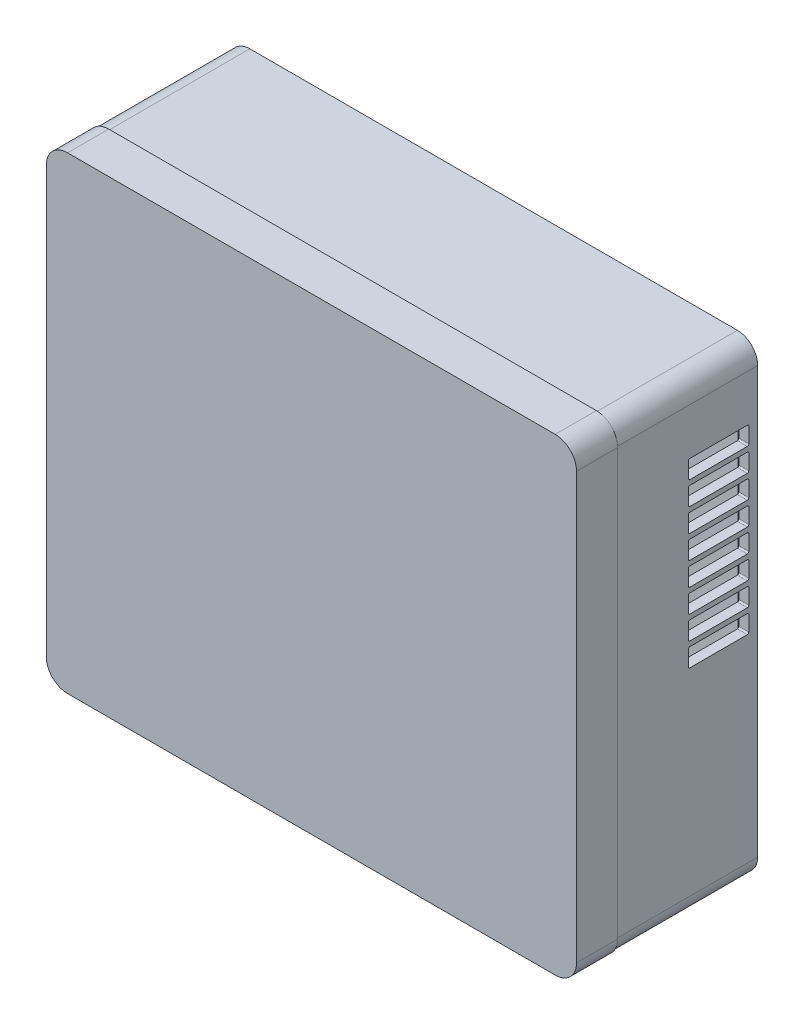
SolidWorks part; units mm, degrees
ref_plane "Front Plane" through (0, 0, 0) normal (0, 0, 1) x (1, 0, 0)
ref_plane "Top Plane" through (0, 0, 0) normal (0, 1, 0) x (1, 0, 0)
ref_plane "Right Plane" through (0, 0, 0) normal (1, 0, 0) x (0, 0, -1)
sketch "Sketch1" plane through (0, 0, 0) normal (0, 0, 1) x (1, 0, 0)
  line L4 (-86.3, 47.45) -> (-86.3, -38.45)
  line L5 (-84, -40.75) -> (14.4, -40.75)
  line L6 (16.7, -38.45) -> (16.7, 47.45)
  line L7 (14.4, 49.75) -> (-84, 49.75)
  line L8 (-86.3, 47.45) -> (-86.3, -38.45)
  line L9 (-84, -40.75) -> (14.4, -40.75)
  line L10 (16.7, -38.45) -> (16.7, 47.45)
  line L11 (14.4, 49.75) -> (-84, 49.75)
  arc A4 (-86.3, -38.45) -> (-84, -40.75) centre (-84, -38.45) ccw
  arc A5 (14.4, -40.75) -> (16.7, -38.45) centre (14.4, -38.45) ccw
  arc A6 (16.7, 47.45) -> (14.4, 49.75) centre (14.4, 47.45) ccw
  arc A7 (-84, 49.75) -> (-86.3, 47.45) centre (-84, 47.45) ccw
  arc A8 (-86.3, -38.45) -> (-84, -40.75) centre (-84, -38.45) ccw
  arc A9 (14.4, -40.75) -> (16.7, -38.45) centre (14.4, -38.45) ccw
  arc A10 (16.7, 47.45) -> (14.4, 49.75) centre (14.4, 47.45) ccw
  arc A11 (-84, 49.75) -> (-86.3, 47.45) centre (-84, 47.45) ccw
  dimension "D1" = 0
extrude "Boss-Extrude1" add sketch "Sketch1" along normal blind 2
sketch "Sketch2" plane through (0, 0, 2) normal (0, 0, 1) x (1, 0, 0)
  line L8 (-88.3, 47.45) -> (-88.3, -38.45)
  line L9 (-84, -42.75) -> (14.4, -42.75)
  line L10 (18.7, -38.45) -> (18.7, 47.45)
  line L11 (14.4, 51.75) -> (-84, 51.75)
  line L12 (-88.3, 47.45) -> (-88.3, -38.45)
  line L13 (-84, -42.75) -> (14.4, -42.75)
  line L14 (18.7, -38.45) -> (18.7, 47.45)
  line L15 (14.4, 51.75) -> (-84, 51.75)
  arc A8 (-84, 51.75) -> (-88.3, 47.45) centre (-84, 47.45) ccw
  arc A9 (-88.3, -38.45) -> (-84, -42.75) centre (-84, -38.45) ccw
  arc A10 (14.4, -42.75) -> (18.7, -38.45) centre (14.4, -38.45) ccw
  arc A11 (18.7, 47.45) -> (14.4, 51.75) centre (14.4, 47.45) ccw
  arc A12 (-84, 51.75) -> (-88.3, 47.45) centre (-84, 47.45) ccw
  arc A13 (-88.3, -38.45) -> (-84, -42.75) centre (-84, -38.45) ccw
  arc A14 (14.4, -42.75) -> (18.7, -38.45) centre (14.4, -38.45) ccw
  arc A15 (18.7, 47.45) -> (14.4, 51.75) centre (14.4, 47.45) ccw
  dimension "D1" = 2
extrude "Boss-Extrude2" add sketch "Sketch2" against normal blind 8.3
sketch "Sketch3" plane through (0, 0, -34.766) normal (0, 0, -1) x (-1, 0, 0)
  line L4 (-14.4, -40.55) -> (84, -40.55)
  line L5 (86.1, -38.45) -> (86.1, 47.45)
  line L6 (84, 49.55) -> (-14.4, 49.55)
  line L7 (-16.5, 47.45) -> (-16.5, -38.45)
  line L8 (-14.4, -40.55) -> (84, -40.55)
  line L9 (86.1, -38.45) -> (86.1, 47.45)
  line L10 (84, 49.55) -> (-14.4, 49.55)
  line L11 (-16.5, 47.45) -> (-16.5, -38.45)
  line L12 (61.7, 0.56) -> (61.7, 38.96)
  line L13 (61.7, 38.96) -> (3.9, 38.96)
  line L14 (3.9, 38.96) -> (3.9, 0.56)
  line L15 (3.9, 0.56) -> (61.7, 0.56)
  line L16 (61.7, 0.56) -> (61.7, 38.96)
  line L17 (61.7, 38.96) -> (3.9, 38.96)
  line L18 (3.9, 38.96) -> (3.9, 0.56)
  line L19 (3.9, 0.56) -> (61.7, 0.56)
  arc A4 (84, -40.55) -> (86.1, -38.45) centre (84, -38.45) ccw
  arc A5 (86.1, 47.45) -> (84, 49.55) centre (84, 47.45) ccw
  arc A6 (-14.4, 49.55) -> (-16.5, 47.45) centre (-14.4, 47.45) ccw
  arc A7 (-16.5, -38.45) -> (-14.4, -40.55) centre (-14.4, -38.45) ccw
  arc A8 (84, -40.55) -> (86.1, -38.45) centre (84, -38.45) ccw
  arc A9 (86.1, 47.45) -> (84, 49.55) centre (84, 47.45) ccw
  arc A10 (-14.4, 49.55) -> (-16.5, 47.45) centre (-14.4, 47.45) ccw
  arc A11 (-16.5, -38.45) -> (-14.4, -40.55) centre (-14.4, -38.45) ccw
  dimension "D1" = 0
  dimension "D2" = 0
extrude "Boss-Extrude3" add sketch "Sketch3" against normal blind 2 separate body
sketch "Sketch4" plane through (0, 0, -34.766) normal (0, 0, -1) x (-1, 0, 0)
  line L8 (-14.4, -42.55) -> (84, -42.55)
  line L9 (88.1, -38.45) -> (88.1, 47.45)
  line L10 (84, 51.55) -> (-14.4, 51.55)
  line L11 (-18.5, 47.45) -> (-18.5, -38.45)
  line L12 (-14.4, -42.55) -> (84, -42.55)
  line L13 (88.1, -38.45) -> (88.1, 47.45)
  line L14 (84, 51.55) -> (-14.4, 51.55)
  line L15 (-18.5, 47.45) -> (-18.5, -38.45)
  line L16 (61.7, 0.56) -> (61.7, 38.96)
  line L17 (61.7, 38.96) -> (3.9, 38.96)
  line L18 (3.9, 38.96) -> (3.9, 0.56)
  line L19 (3.9, 0.56) -> (61.7, 0.56)
  line L20 (61.7, 0.56) -> (61.7, 38.96)
  line L21 (61.7, 38.96) -> (3.9, 38.96)
  line L22 (3.9, 38.96) -> (3.9, 0.56)
  line L23 (3.9, 0.56) -> (61.7, 0.56)
  line L24 (-14.4, -40.55) -> (84, -40.55)
  line L25 (86.1, -38.45) -> (86.1, 47.45)
  line L26 (84, 49.55) -> (-14.4, 49.55)
  line L27 (-16.5, 47.45) -> (-16.5, -38.45)
  line L28 (-14.4, -40.55) -> (84, -40.55)
  line L29 (86.1, -38.45) -> (86.1, 47.45)
  line L30 (84, 49.55) -> (-14.4, 49.55)
  line L31 (-16.5, 47.45) -> (-16.5, -38.45)
  arc A8 (-18.5, -38.45) -> (-14.4, -42.55) centre (-14.4, -38.45) ccw
  arc A9 (84, -42.55) -> (88.1, -38.45) centre (84, -38.45) ccw
  arc A10 (88.1, 47.45) -> (84, 51.55) centre (84, 47.45) ccw
  arc A11 (-14.4, 51.55) -> (-18.5, 47.45) centre (-14.4, 47.45) ccw
  arc A12 (-18.5, -38.45) -> (-14.4, -42.55) centre (-14.4, -38.45) ccw
  arc A13 (84, -42.55) -> (88.1, -38.45) centre (84, -38.45) ccw
  arc A14 (88.1, 47.45) -> (84, 51.55) centre (84, 47.45) ccw
  arc A15 (-14.4, 51.55) -> (-18.5, 47.45) centre (-14.4, 47.45) ccw
  arc A16 (-16.5, -38.45) -> (-14.4, -40.55) centre (-14.4, -38.45) ccw
  arc A17 (84, -40.55) -> (86.1, -38.45) centre (84, -38.45) ccw
  arc A18 (86.1, 47.45) -> (84, 49.55) centre (84, 47.45) ccw
  arc A19 (-14.4, 49.55) -> (-16.5, 47.45) centre (-14.4, 47.45) ccw
  arc A20 (-16.5, -38.45) -> (-14.4, -40.55) centre (-14.4, -38.45) ccw
  arc A21 (84, -40.55) -> (86.1, -38.45) centre (84, -38.45) ccw
  arc A22 (86.1, 47.45) -> (84, 49.55) centre (84, 47.45) ccw
  arc A23 (-14.4, 49.55) -> (-16.5, 47.45) centre (-14.4, 47.45) ccw
  arc M13 (-16.5, -38.45) -> (-14.4, -40.55) centre (-14.4, -38.45) ccw
  line M14 (-14.4, -40.55) -> (84, -40.55)
  arc M15 (84, -40.55) -> (86.1, -38.45) centre (84, -38.45) ccw
  line M16 (86.1, -38.45) -> (86.1, 47.45)
  arc M17 (86.1, 47.45) -> (84, 49.55) centre (84, 47.45) ccw
  line M18 (84, 49.55) -> (-14.4, 49.55)
  arc M19 (-14.4, 49.55) -> (-16.5, 47.45) centre (-14.4, 47.45) ccw
  line M20 (-16.5, 47.45) -> (-16.5, -38.45)
  dimension "D1" = 2
  dimension "D2" = 0
  dimension "D3" = 0
extrude "Boss-Extrude6" add sketch "Sketch4" along direction (0, 0, 1) on the side against the normal blind 30 contours L14 A15 L15 A12 L12 A13 L13 A14 M13 M20 M19 M18 M17 M16 M15 M14
sketch "Sketch5" plane through (0, -42.55, 0) normal (0, -1, 0) x (1, 0, 0)
  line L4 (13.85, -17.47) -> (13.85, -6.47)
  line L5 (13.85, -6.47) -> (4.55, -6.47)
  line L6 (4.55, -6.47) -> (4.55, -17.47)
  line L7 (4.55, -17.47) -> (13.85, -17.47)
  line L8 (13.85, -17.47) -> (13.85, -6.47)
  line L9 (13.85, -6.47) -> (4.55, -6.47)
  line L10 (4.55, -6.47) -> (4.55, -17.47)
  line L11 (4.55, -17.47) -> (13.85, -17.47)
  line L12 (1.288, -13.3562) -> (1.288, -6.5462)
  line L13 (1.288, -6.5462) -> (-16.408, -6.5462)
  line L14 (-16.408, -6.5462) -> (-16.408, -13.3562)
  line L15 (-16.408, -13.3562) -> (1.288, -13.3562)
  line L16 (1.288, -13.3562) -> (1.288, -6.5462)
  line L17 (1.288, -6.5462) -> (-16.408, -6.5462)
  line L18 (-16.408, -6.5462) -> (-16.408, -13.3562)
  line L19 (-16.408, -13.3562) -> (1.288, -13.3562)
  line L20 (-20.375, -23.3862) -> (-20.375, -6.5462)
  line L21 (-20.375, -6.5462) -> (-34.425, -6.5462)
  line L22 (-34.425, -6.5462) -> (-34.425, -23.3862)
  line L23 (-34.425, -23.3862) -> (-20.375, -23.3862)
  line L24 (-20.375, -23.3862) -> (-20.375, -6.5462)
  line L25 (-20.375, -6.5462) -> (-34.425, -6.5462)
  line L26 (-34.425, -6.5462) -> (-34.425, -23.3862)
  line L27 (-34.425, -23.3862) -> (-20.375, -23.3862)
  line L28 (-37.375, -23.3862) -> (-37.375, -6.5462)
  line L29 (-37.375, -6.5462) -> (-51.425, -6.5462)
  line L30 (-51.425, -6.5462) -> (-51.425, -23.3862)
  line L31 (-51.425, -23.3862) -> (-37.375, -23.3862)
  line L32 (-37.375, -23.3862) -> (-37.375, -6.5462)
  line L33 (-37.375, -6.5462) -> (-51.425, -6.5462)
  line L34 (-51.425, -6.5462) -> (-51.425, -23.3862)
  line L35 (-51.425, -23.3862) -> (-37.375, -23.3862)
  line L36 (-72.33, -9.9762) -> (-72.33, -6.5462)
  line L37 (-72.33, -6.5462) -> (-81.22, -6.5462)
  line L38 (-81.22, -6.5462) -> (-81.22, -9.9762)
  line L39 (-81.22, -9.9762) -> (-72.33, -9.9762)
  line L40 (-72.33, -9.9762) -> (-72.33, -6.5462)
  line L41 (-72.33, -6.5462) -> (-81.22, -6.5462)
  line L42 (-81.22, -6.5462) -> (-81.22, -9.9762)
  line L43 (-81.22, -9.9762) -> (-72.33, -9.9762)
  line L44 (-57.38, -20.12) -> (-57.38, -6.47)
  line L45 (-57.38, -6.47) -> (-66.12, -6.47)
  line L46 (-66.12, -6.47) -> (-66.12, -20.12)
  line L47 (-66.12, -20.12) -> (-57.38, -20.12)
  line L48 (-57.38, -20.12) -> (-57.38, -6.47)
  line L49 (-57.38, -6.47) -> (-66.12, -6.47)
  line L50 (-66.12, -6.47) -> (-66.12, -20.12)
  line L51 (-66.12, -20.12) -> (-57.38, -20.12)
  line L52 (-55.38, -20.12) -> (-55.38, -6.47)
  line L53 (-55.38, -6.47) -> (-57.38, -6.47)
  line L54 (-57.38, -6.47) -> (-57.38, -20.12)
  line L55 (-57.38, -20.12) -> (-55.38, -20.12)
  line L56 (-55.38, -20.12) -> (-55.38, -6.47)
  line L57 (-55.38, -6.47) -> (-57.38, -6.47)
  line L58 (-57.38, -6.47) -> (-57.38, -20.12)
  line L59 (-57.38, -20.12) -> (-55.38, -20.12)
  line L60 (-53.673, -20.12) -> (-53.673, -6.47)
  line L61 (-53.673, -6.47) -> (-55.38, -6.47)
  line L62 (-55.38, -6.47) -> (-55.38, -20.12)
  line L63 (-55.38, -20.12) -> (-53.673, -20.12)
  line L64 (-53.673, -20.12) -> (-53.673, -6.47)
  line L65 (-53.673, -6.47) -> (-55.38, -6.47)
  line L66 (-55.38, -6.47) -> (-55.38, -20.12)
  line L67 (-55.38, -20.12) -> (-53.673, -20.12)
  line L68 (-66.12, -20.12) -> (-66.12, -6.47)
  line L69 (-66.12, -6.47) -> (-68.12, -6.47)
  line L70 (-68.12, -6.47) -> (-68.12, -20.12)
  line L71 (-68.12, -20.12) -> (-66.12, -20.12)
  line L72 (-66.12, -20.12) -> (-66.12, -6.47)
  line L73 (-66.12, -6.47) -> (-68.12, -6.47)
  line L74 (-68.12, -6.47) -> (-68.12, -20.12)
  line L75 (-68.12, -20.12) -> (-66.12, -20.12)
  line L76 (-68.12, -20.12) -> (-68.12, -6.47)
  line L77 (-68.12, -6.47) -> (-69.827, -6.47)
  line L78 (-69.827, -6.47) -> (-69.827, -20.12)
  line L79 (-69.827, -20.12) -> (-68.12, -20.12)
  line L80 (-68.12, -20.12) -> (-68.12, -6.47)
  line L81 (-68.12, -6.47) -> (-69.827, -6.47)
  line L82 (-69.827, -6.47) -> (-69.827, -20.12)
  line L83 (-69.827, -20.12) -> (-68.12, -20.12)
  dimension "D1" = 0
  dimension "D2" = 0
  dimension "D3" = 0
  dimension "D4" = 0
  dimension "D5" = 0
  dimension "D6" = 0
  dimension "D7" = 0
  dimension "D8" = 0
  dimension "D9" = 0
  dimension "D10" = 0
extrude "Cut-Extrude1" cut sketch "Sketch5" against normal blind 2 contours L26 L27 L24 L25 | L18 L19 L16 L17 | L10 L11 L8 L9 | L34 L35 L32 L33 | L50 L51 L48 L49 | L42 L43 L40 L41 | L82 L83 L74 L81 | L74 L75 L50 L73 | L56 L67 L64 L65
sketch "Sketch6" plane through (18.5, 0, 0) normal (1, 0, 0) x (0, 0, -1)
  line L0 (32.966, 1.76) -> (32.966, 4.86) construction
  line L1 (32.666, 1.46) -> (21.066, 1.46) construction
  line L2 (32.666, 5.16) -> (21.066, 5.16) construction
  line L3 (20.766, 4.86) -> (20.766, 1.76) construction
  line L4 (32.966, 1.76) -> (32.966, 4.86)
  line L5 (32.666, 1.46) -> (21.066, 1.46)
  line L6 (32.666, 5.16) -> (21.066, 5.16)
  line L7 (20.766, 4.86) -> (20.766, 1.76)
  arc A0 (32.966, 4.86) -> (32.666, 5.16) centre (32.666, 4.86) ccw construction
  arc A1 (32.666, 1.46) -> (32.966, 1.76) centre (32.666, 1.76) ccw construction
  arc A2 (20.766, 1.76) -> (21.066, 1.46) centre (21.066, 1.76) ccw construction
  arc A3 (21.066, 5.16) -> (20.766, 4.86) centre (21.066, 4.86) ccw construction
  arc A4 (32.966, 4.86) -> (32.666, 5.16) centre (32.666, 4.86) ccw
  arc A5 (32.666, 1.46) -> (32.966, 1.76) centre (32.666, 1.76) ccw
  arc A6 (20.766, 1.76) -> (21.066, 1.46) centre (21.066, 1.76) ccw
  arc A7 (21.066, 5.16) -> (20.766, 4.86) centre (21.066, 4.86) ccw
extrude "Cut-Extrude2" cut sketch "Sketch6" against normal blind 2
sketch "Sketch7" plane through (18.5, 0, 0) normal (1, 0, 0) x (0, 0, -1)
  line L1 (32.666, 28.66) -> (21.066, 28.66) construction
  line L2 (32.966, 25.26) -> (32.966, 28.36) construction
  line L3 (32.666, 24.96) -> (21.066, 24.96) construction
  line L4 (32.966, 20.56) -> (32.966, 23.66) construction
  line L5 (32.666, 23.96) -> (21.066, 23.96) construction
  line L6 (32.666, 20.26) -> (21.066, 20.26) construction
  line L7 (32.966, 15.86) -> (32.966, 18.96) construction
  line L8 (32.666, 15.56) -> (21.066, 15.56) construction
  line L9 (20.766, 18.96) -> (20.766, 15.86) construction
  line L10 (32.666, 19.26) -> (21.066, 19.26) construction
  line L11 (32.966, 11.16) -> (32.966, 14.26) construction
  line L12 (20.766, 14.26) -> (20.766, 11.16) construction
  line L13 (20.766, 12.3089) -> (20.766, 14.6156) construction
  line L14 (32.666, 14.56) -> (21.066, 14.56) construction
  line L15 (32.666, 10.86) -> (21.066, 10.86) construction
  line L16 (32.966, 6.46) -> (32.966, 9.56) construction
  line L17 (32.666, 9.86) -> (21.066, 9.86) construction
  line L18 (20.766, 9.56) -> (20.766, 6.46) construction
  line L19 (32.666, 6.16) -> (21.066, 6.16) construction
  line L20 (20.766, 28.36) -> (20.766, 25.26)
  line L21 (32.666, 28.66) -> (21.066, 28.66)
  line L22 (32.966, 25.26) -> (32.966, 28.36)
  line L23 (32.666, 24.96) -> (21.066, 24.96)
  line L24 (32.966, 20.56) -> (32.966, 23.66)
  line L25 (32.666, 23.96) -> (21.066, 23.96)
  line L26 (32.666, 20.26) -> (21.066, 20.26)
  line L27 (32.966, 15.86) -> (32.966, 18.96)
  line L28 (32.666, 15.56) -> (21.066, 15.56)
  line L29 (20.766, 18.96) -> (20.766, 15.86)
  line L30 (32.666, 19.26) -> (21.066, 19.26)
  line L31 (32.966, 11.16) -> (32.966, 14.26)
  line L32 (20.766, 14.26) -> (20.766, 11.16)
  line L33 (20.766, 12.3089) -> (20.766, 14.6156)
  line L34 (32.666, 14.56) -> (21.066, 14.56)
  line L35 (32.666, 10.86) -> (21.066, 10.86)
  line L36 (32.966, 6.46) -> (32.966, 9.56)
  line L37 (32.666, 9.86) -> (21.066, 9.86)
  line L38 (20.766, 9.56) -> (20.766, 6.46)
  line L39 (32.666, 6.16) -> (21.066, 6.16)
  line L40 (20.766, 23.66) -> (20.766, 20.56)
  arc A0 (21.066, 28.66) -> (20.766, 28.36) centre (21.066, 28.36) ccw construction
  arc A1 (32.966, 28.36) -> (32.666, 28.66) centre (32.666, 28.36) ccw construction
  arc A2 (32.666, 24.96) -> (32.966, 25.26) centre (32.666, 25.26) ccw construction
  arc A3 (32.966, 23.66) -> (32.666, 23.96) centre (32.666, 23.66) ccw construction
  arc A4 (32.666, 20.26) -> (32.966, 20.56) centre (32.666, 20.56) ccw construction
  arc A5 (20.766, 25.26) -> (21.066, 24.96) centre (21.066, 25.26) ccw construction
  arc A6 (20.766, 20.56) -> (21.066, 20.26) centre (21.066, 20.56) ccw construction
  arc A7 (21.066, 23.96) -> (20.766, 23.66) centre (21.066, 23.66) ccw construction
  arc A8 (20.766, 15.86) -> (21.066, 15.56) centre (21.066, 15.86) ccw construction
  arc A9 (21.066, 19.26) -> (20.766, 18.96) centre (21.066, 18.96) ccw construction
  arc A10 (32.966, 18.96) -> (32.666, 19.26) centre (32.666, 18.96) ccw construction
  arc A11 (32.666, 15.56) -> (32.966, 15.86) centre (32.666, 15.86) ccw construction
  arc A12 (32.666, 10.86) -> (32.966, 11.16) centre (32.666, 11.16) ccw construction
  arc A13 (32.966, 14.26) -> (32.666, 14.56) centre (32.666, 14.26) ccw construction
  arc A14 (20.766, 11.16) -> (21.066, 10.86) centre (21.066, 11.16) ccw construction
  arc A15 (21.066, 14.56) -> (20.766, 14.26) centre (21.066, 14.26) ccw construction
  arc A16 (32.666, 6.16) -> (32.966, 6.46) centre (32.666, 6.46) ccw construction
  arc A17 (32.966, 9.56) -> (32.666, 9.86) centre (32.666, 9.56) ccw construction
  arc A18 (21.066, 9.86) -> (20.766, 9.56) centre (21.066, 9.56) ccw construction
  arc A19 (20.766, 6.46) -> (21.066, 6.16) centre (21.066, 6.46) ccw construction
  arc A20 (21.066, 28.66) -> (20.766, 28.36) centre (21.066, 28.36) ccw
  arc A21 (32.966, 28.36) -> (32.666, 28.66) centre (32.666, 28.36) ccw
  arc A22 (32.666, 24.96) -> (32.966, 25.26) centre (32.666, 25.26) ccw
  arc A23 (32.966, 23.66) -> (32.666, 23.96) centre (32.666, 23.66) ccw
  arc A24 (32.666, 20.26) -> (32.966, 20.56) centre (32.666, 20.56) ccw
  arc A25 (20.766, 25.26) -> (21.066, 24.96) centre (21.066, 25.26) ccw
  arc A26 (20.766, 20.56) -> (21.066, 20.26) centre (21.066, 20.56) ccw
  arc A27 (21.066, 23.96) -> (20.766, 23.66) centre (21.066, 23.66) ccw
  arc A28 (20.766, 15.86) -> (21.066, 15.56) centre (21.066, 15.86) ccw
  arc A29 (21.066, 19.26) -> (20.766, 18.96) centre (21.066, 18.96) ccw
  arc A30 (32.966, 18.96) -> (32.666, 19.26) centre (32.666, 18.96) ccw
  arc A31 (32.666, 15.56) -> (32.966, 15.86) centre (32.666, 15.86) ccw
  arc A32 (32.666, 10.86) -> (32.966, 11.16) centre (32.666, 11.16) ccw
  arc A33 (32.966, 14.26) -> (32.666, 14.56) centre (32.666, 14.26) ccw
  arc A34 (20.766, 11.16) -> (21.066, 10.86) centre (21.066, 11.16) ccw
  arc A35 (21.066, 14.56) -> (20.766, 14.26) centre (21.066, 14.26) ccw
  arc A36 (32.666, 6.16) -> (32.966, 6.46) centre (32.666, 6.46) ccw
  arc A37 (32.966, 9.56) -> (32.666, 9.86) centre (32.666, 9.56) ccw
  arc A38 (21.066, 9.86) -> (20.766, 9.56) centre (21.066, 9.56) ccw
  arc A39 (20.766, 6.46) -> (21.066, 6.16) centre (21.066, 6.46) ccw
extrude "Cut-Extrude3" cut sketch "Sketch7" against normal blind 2 contours L20 A25 L23 A22 L22 A21 L21 A20 | L25 A27 L40 A26 L26 A24 L24 A23 | L28 A31 L27 A30 L30 A29 L29 A28 | L34 A35 L32 A34 L35 A32 L31 A33 | L38 A39 L39 A36 L36 A37 L37 A38
ref_plane "Plane1" through (-3.9, 29.66, -32.666) normal (0, 0, -1) x (-1, 0, 0)
sketch "Sketch10" plane through (18.5, 0, 0) normal (1, 0, 0) x (0, 0, -1)
  line L0 (32.966, 34.66) -> (32.966, 37.76) construction
  line L1 (20.766, 37.76) -> (20.766, 34.66) construction
  line L2 (32.666, 38.06) -> (21.066, 38.06) construction
  line L3 (21.066, 34.36) -> (32.666, 34.36) construction
  line L12 (20.766, 33.06) -> (20.766, 29.96) construction
  line L13 (21.066, 29.66) -> (32.666, 29.66) construction
  line L14 (32.966, 29.96) -> (32.966, 33.06) construction
  line L15 (32.666, 33.36) -> (21.066, 33.36) construction
  line L16 (32.966, 34.66) -> (32.966, 37.76)
  line L17 (20.766, 37.76) -> (20.766, 34.66)
  line L18 (32.666, 38.06) -> (21.066, 38.06)
  line L19 (21.066, 34.36) -> (32.666, 34.36)
  line L20 (20.766, 33.06) -> (20.766, 29.96)
  line L21 (21.066, 29.66) -> (32.666, 29.66)
  line L22 (32.966, 29.96) -> (32.966, 33.06)
  line L23 (32.666, 33.36) -> (21.066, 33.36)
  arc A0 (32.966, 37.76) -> (32.666, 38.06) centre (32.666, 37.76) ccw construction
  arc A1 (32.666, 34.36) -> (32.966, 34.66) centre (32.666, 34.66) ccw construction
  arc A2 (20.766, 34.66) -> (21.066, 34.36) centre (21.066, 34.66) ccw construction
  arc A3 (21.066, 38.06) -> (20.766, 37.76) centre (21.066, 37.76) ccw construction
  arc A4 (21.066, 33.36) -> (20.766, 33.06) centre (21.066, 33.06) ccw construction
  arc A5 (20.766, 29.96) -> (21.066, 29.66) centre (21.066, 29.96) ccw construction
  arc A6 (32.666, 29.66) -> (32.966, 29.96) centre (32.666, 29.96) ccw construction
  arc A7 (32.966, 33.06) -> (32.666, 33.36) centre (32.666, 33.06) ccw construction
  arc A8 (32.966, 37.76) -> (32.666, 38.06) centre (32.666, 37.76) ccw
  arc A9 (32.666, 34.36) -> (32.966, 34.66) centre (32.666, 34.66) ccw
  arc A10 (20.766, 34.66) -> (21.066, 34.36) centre (21.066, 34.66) ccw
  arc A11 (21.066, 38.06) -> (20.766, 37.76) centre (21.066, 37.76) ccw
  arc A12 (21.066, 33.36) -> (20.766, 33.06) centre (21.066, 33.06) ccw
  arc A13 (20.766, 29.96) -> (21.066, 29.66) centre (21.066, 29.96) ccw
  arc A14 (32.666, 29.66) -> (32.966, 29.96) centre (32.666, 29.96) ccw
  arc A15 (32.966, 33.06) -> (32.666, 33.36) centre (32.666, 33.06) ccw
extrude "Cut-Extrude4" cut sketch "Sketch10" against normal blind 2
